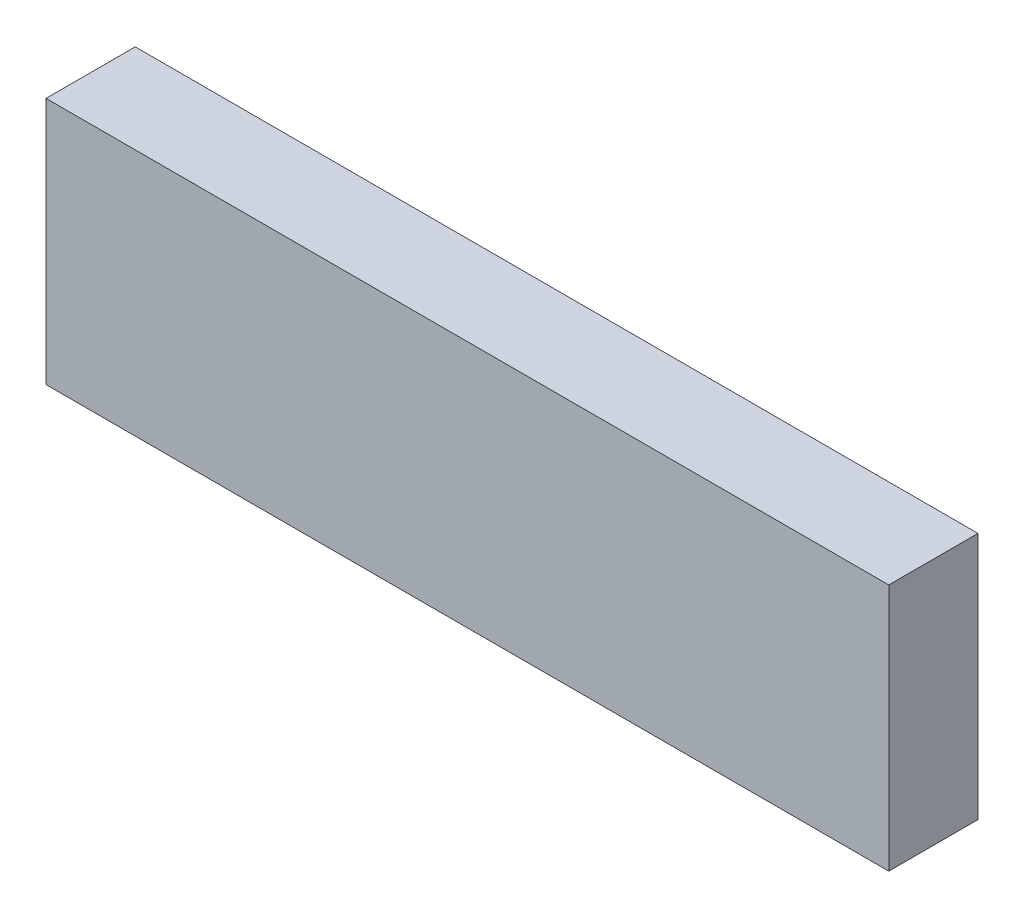
SolidWorks part; units mm, degrees
ref_plane "Front Plane" through (0, 0, 0) normal (0, 0, 1) x (1, 0, 0)
ref_plane "Top Plane" through (0, 0, 0) normal (0, 1, 0) x (1, 0, 0)
ref_plane "Right Plane" through (0, 0, 0) normal (1, 0, 0) x (0, 0, -1)
sketch "Sketch1" plane through (0, 0, 0) normal (0, 1, 0) x (1, 0, 0)
  line L1 (0, 0) -> (215.9, 0)
  line L2 (0, 0) -> (0, 22.86)
  line L3 (0, 22.86) -> (215.9, 22.86)
  line L4 (215.9, 0) -> (215.9, 22.86)
  dimension "D1" = 215.9
  dimension "D2" = 22.86
extrude "Boss-Extrude1" add sketch "Sketch1" along normal blind 63.5
